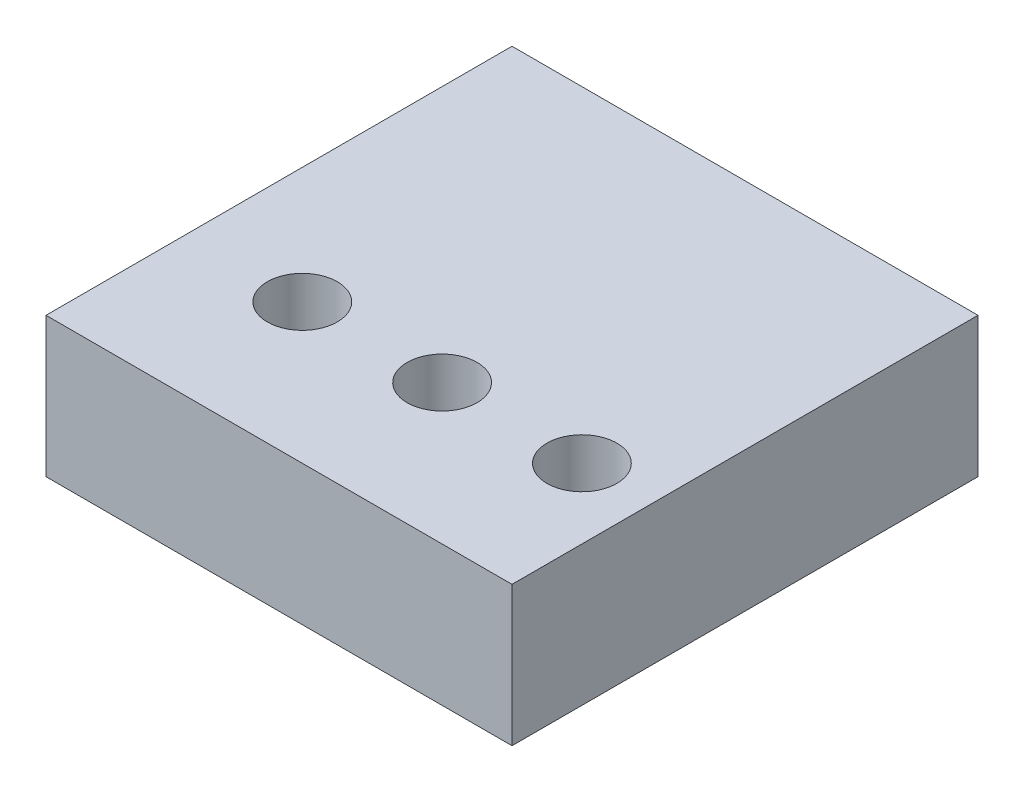
SolidWorks part; units mm, degrees
ref_plane "正面" through (0, 0, 0) normal (0, 0, 1) x (1, 0, 0)
ref_plane "平面" through (0, 0, 0) normal (0, 1, 0) x (1, 0, 0)
ref_plane "右側面" through (0, 0, 0) normal (1, 0, 0) x (0, 0, -1)
sketch "ｽｹｯﾁ1" plane through (0, 0, 0) normal (0, 1, 0) x (1, 0, 0)
  line L1 (0, 0) -> (100, 0)
  line L2 (0, 0) -> (0, 100)
  line L3 (0, 100) -> (100, 100)
  line L4 (100, 0) -> (100, 100)
  dimension "D1" = 100
  dimension "D2" = 100
extrude "押し出し1" add sketch "ｽｹｯﾁ1" along normal blind 30
sketch "ｽｹｯﾁ2" plane through (0, 30, 0) normal (0, 1, 0) x (-1, 0, 0)
  line L0 (0, -30) -> (-100, -30) construction
  line L1 (0, -100) -> (0, 0) construction
  line L2 (-100, 0) -> (-100, -100) construction
  line L3 (-55, 0) -> (-55, -100) construction
  line L4 (0, 0) -> (-100, 0) construction
  line L5 (-100, -100) -> (0, -100) construction
  line L6 (-25, -100) -> (-25, 0) construction
  line L7 (-85, -100) -> (-85, 0) construction
  circle A0 centre (-55, -30) radius 7.5
  circle A1 centre (-25, -30) radius 7.5
  circle A2 centre (-85, -30) radius 7.5
  dimension "D3" = 15
  dimension "D6" = 15
  dimension "D7" = 15
  dimension "D1" = 30
  dimension "D2" = 45
  dimension "D4" = 15
  dimension "D5" = 30
extrude "ｶｯﾄ - 押し出し1" cut sketch "ｽｹｯﾁ2" against normal blind 30
